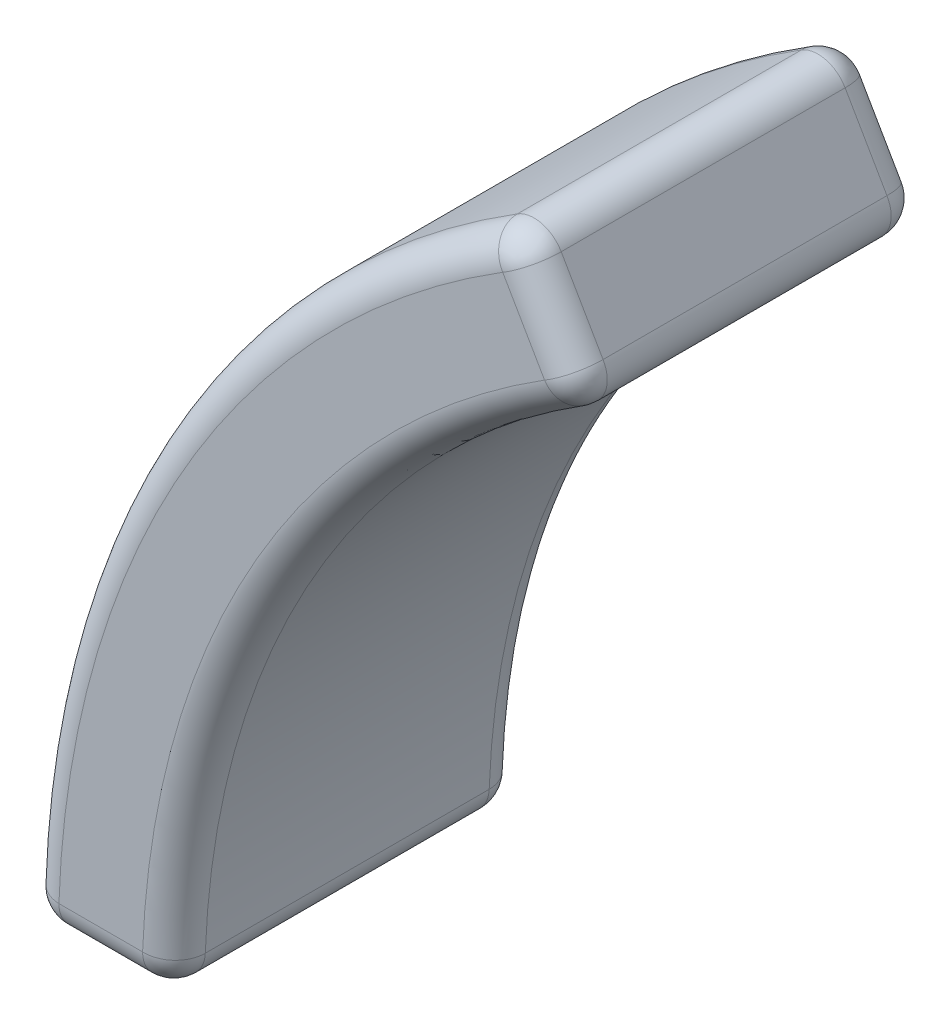
SolidWorks part; units mm, degrees
ref_plane "Front Plane" through (0, 0, 0) normal (0, 0, 1) x (1, 0, 0)
ref_plane "Top Plane" through (0, 0, 0) normal (0, 1, 0) x (1, 0, 0)
ref_plane "Right Plane" through (0, 0, 0) normal (1, 0, 0) x (0, 0, -1)
sketch "Sketch1" plane through (0, 0, 0) normal (0, 0, 1) x (1, 0, 0)
  line L0 (-791.6, 0) -> (-931.6, 0)
  line L1 (-395.8, 685.5457) -> (-465.8, 806.7893)
  arc A0 (-465.8, 806.7893) -> (-931.6, 0) centre (0, 0) ccw
  arc A1 (-395.8, 685.5457) -> (-791.6, 0) centre (0, 0) ccw
  dimension "D1" = 1863.2
  dimension "D2" = 140
  dimension "D3" = 60
extrude "Boss-Extrude1" add sketch "Sketch1" against normal blind 331.6
fillet "Fillet1" radius 30 12 edges at (-430.8, 746.1675, -331.6) (-465.8, 806.7893, -165.8) (-395.8, 685.5457, -165.8) (-430.8, 746.1675, 0) (-806.7893, 465.8, -331.6) (-806.7893, 465.8, 0) (-685.5457, 395.8, 0) (-685.5457, 395.8, -331.6) (-861.6, 0, -331.6) (-861.6, 0, 0) (-931.6, 0, -165.8) (-791.6, 0, -165.8)
